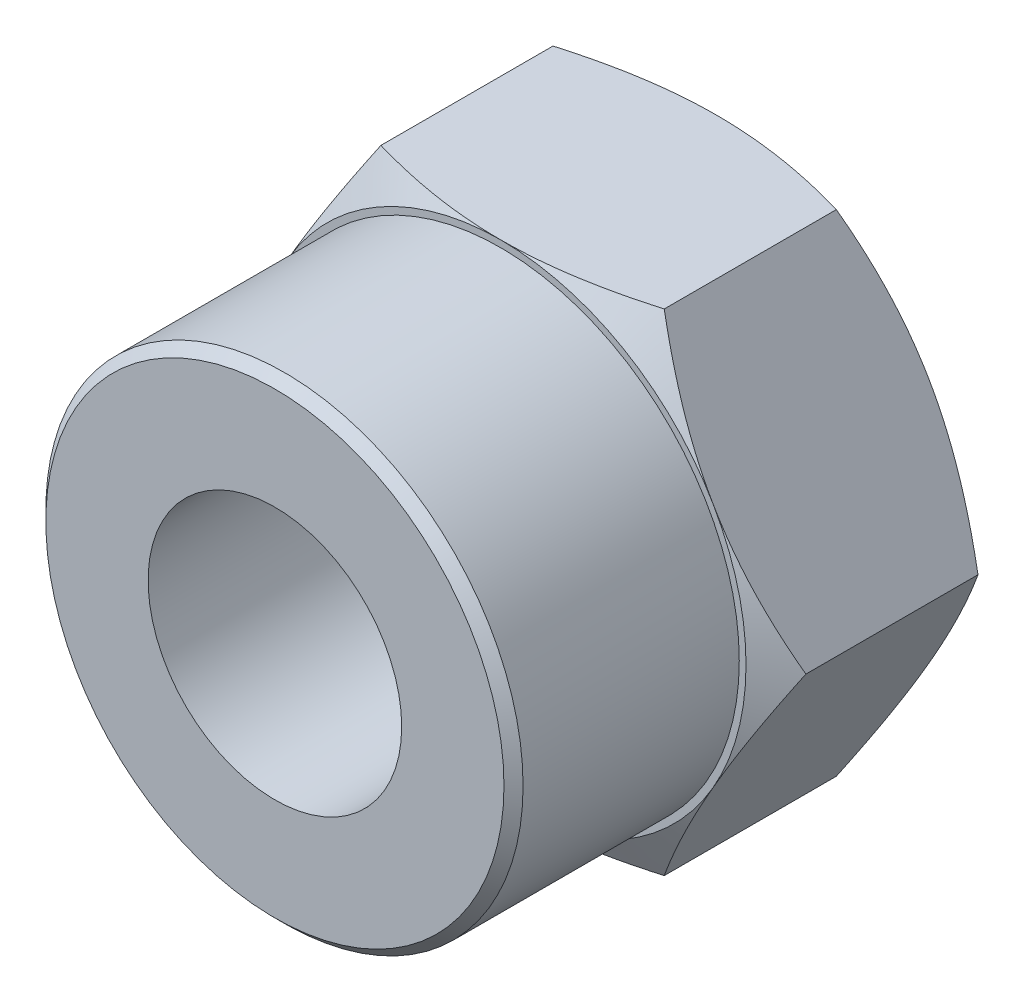
SolidWorks part; units mm, degrees
ref_plane "Front" through (0, 0, 0) normal (0, 0, 1) x (1, 0, 0)
ref_plane "Top" through (0, 0, 0) normal (0, 1, 0) x (1, 0, 0)
ref_plane "Right" through (0, 0, 0) normal (1, 0, 0) x (0, 0, -1)
sketch "Sketch1" plane through (0, 0, 0) normal (0, 0, 1) x (1, 0, 0)
  line L1 (2.3094, -4) -> (4.6188, 0)
  line L2 (4.6188, 0) -> (2.3094, 4)
  line L3 (2.3094, 4) -> (-2.3094, 4)
  line L4 (-2.3094, 4) -> (-4.6188, 0)
  line L5 (-4.6188, 0) -> (-2.3094, -4)
  line L6 (-2.3094, -4) -> (2.3094, -4)
  circle A0 centre (0, 0) radius 4 construction
  circle A1 centre (0, 0) radius 2.067
  dimension "xd" = 4.134
  dimension "s" = 8
extrude "BaseNut" add sketch "Sketch1" against normal blind 3.52
cosmetic thread "ThreadCosmetic1" [suppressed] parameters "m"=29.4, "D2"=5
sketch "Sketch3" plane through (0, 0, 0) normal (0, 1, 0) x (1, 0, 0)
  line L0 (0, 16.3108) -> (0, -16.1137) construction
  line L2 (-2.0696, 1.76) -> (33.5085, 1.76) construction
  line L3 (4, 3.52) -> (4.6188, 3.52)
  line L5 (4.6188, 3.52) -> (4.6188, 3.1627)
  line L7 (4.6188, 3.1627) -> (4, 3.52)
  line L8 (4.6188, 0.3573) -> (4, 0)
  line L9 (4.6188, 0) -> (4.6188, 0.3573)
  line L10 (4, 0) -> (4.6188, 0)
  dimension "D1" = 30
  dimension "s1" = 8
revolve "Double-Chamfer" cut sketch "Sketch3" angle 360 about L0
sketch "Sketch2" plane through (19.1814, 9.5168, 0) normal (0, 0, 1) x (1, 0, 0)
  circle A1 centre (-19.1814, -9.5168) radius 2.067 construction
  circle A2 centre (-19.1814, -9.5168) radius 3.89
  circle A3 centre (-19.1814, -9.5168) radius 2.067
  dimension "s1" = 7.78
extrude "Extrude1" add sketch "Sketch2" along normal offset from surface (3.68 mm away) 7.2 up to face at (2.067, 0, -3.52)
sketch "Sketch5" plane through (0, 0, 0) normal (0, 1, 0) x (1, 0, 0)
  line L0 (0, 16.8008) -> (0, -2.8116) construction
  line L2 (2.067, 3.52) -> (2.875, 3.52)
  line L5 (2.875, 3.52) -> (2.067, 3.0535)
  line L7 (2.067, 3.0535) -> (2.067, 3.52)
  dimension "D1" = 30
  dimension "da" = 5.75
revolve "EndChamfer" cut sketch "Sketch5" angle 360 about L0
chamfer "Chamfer1" distance 0.1556 angle 45 1 edges at (3.89, 0, 3.68)
sketch "Sketch6" plane through (0, 0, 0) normal (0, 1, 0) x (1, 0, 0)
  line L0 (0, -21.8676) -> (0, 36.2739) construction
  line L1 (-2.442, 3.0535) -> (-2.067, 2.837)
  line L2 (-2.067, 2.837) -> (-1.634, 2.837)
  line L3 (-1.634, 2.837) -> (-1.634, 3.27)
  line L4 (-1.634, 3.27) -> (-2.067, 3.27)
  line L5 (-2.067, 3.27) -> (-2.442, 3.0535)
  dimension "D1" = 0.433
  dimension "D2" = 4.134
revolve "Cut-Revolve10" [suppressed] cut sketch "Sketch6" angle 360 about L0
pattern_linear "LPattern10" [suppressed] count 7 spacing 0.5196 along (0, 0, -1)
equation "\"D1@Chamfer1\" = \"s1@Sketch2\" / 50"
equation "\"s1@Sketch3\" = \"s@Sketch1\""
equation "\"D2@Sketch6\" = \"xd@Sketch1\""
equation "\"D1@Sketch6\" =  ( \"D2@ThreadCosmetic1\"  - \"xd@Sketch1\")  / 2"
equation "\"D3@LPattern10\" = \"D1@Sketch6\" * 1.2"
equation "\"D1@LPattern10\" = \"m@BaseNut\" / \"D3@LPattern10\""
